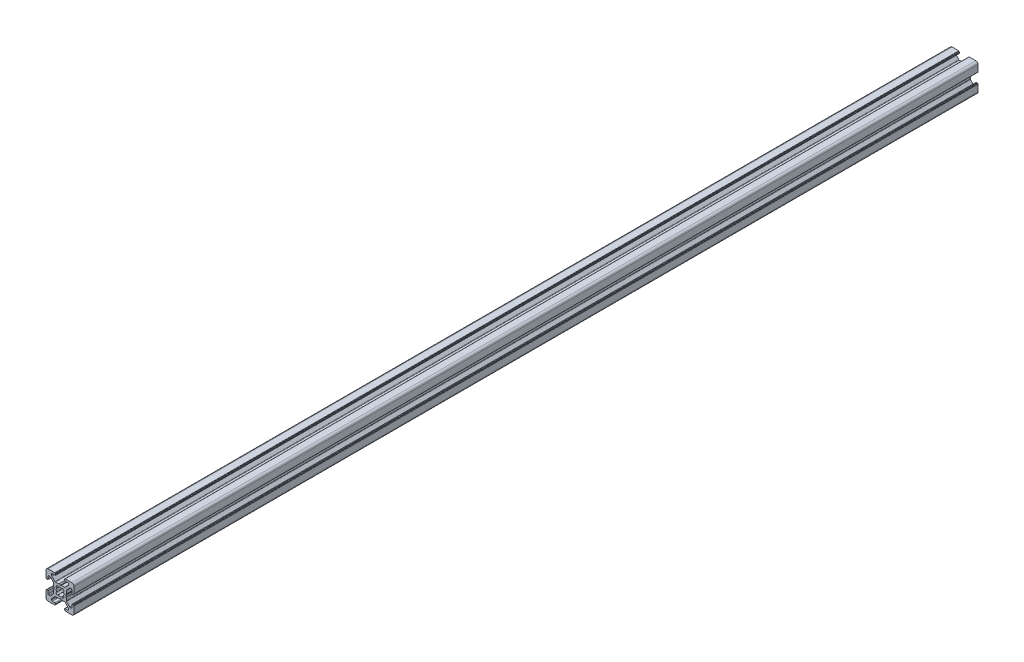
SolidWorks part; units mm, degrees
material "3.1355 (EN-AW 2024)"
ref_plane "Спереди" through (0, 0, 0) normal (0, 0, 1) x (1, 0, 0)
ref_plane "Сверху" through (0, 0, 0) normal (0, 1, 0) x (1, 0, 0)
ref_plane "Справа" through (0, 0, 0) normal (1, 0, 0) x (0, 0, -1)
sketch "Model" plane through (0, 0, 0) normal (0, 0, 1) x (1, 0, 0)
  line L0 (-1.9139, 2.9896) -> (-1.2582, 2.4453)
  line L1 (1.2582, 2.4453) -> (1.9139, 2.9896)
  line L2 (2.9922, 1.9099) -> (2.4453, 1.2582)
  line L3 (2.4453, -1.2582) -> (2.9922, -1.9099)
  line L4 (1.9139, -2.9896) -> (1.2582, -2.4453)
  line L5 (-1.2582, -2.4453) -> (-1.9139, -2.9896)
  line L6 (-2.9922, -1.9099) -> (-2.4453, -1.2582)
  line L7 (-2.4453, 1.2582) -> (-2.9922, 1.9099)
  line L8 (5.6579, 4.5972) -> (5.7096, 4.7904)
  line L9 (5.7096, 4.7904) -> (5.9028, 4.8421)
  line L10 (5.9028, 4.8421) -> (6.9142, 5.8536)
  line L11 (7.2678, 6) -> (8, 6)
  line L12 (8.5, 5.5) -> (8.5, 3.6)
  line L13 (9, 3.1) -> (9.3, 3.1)
  line L14 (9.5, 3.3) -> (9.5, 3.35)
  line L15 (9.7, 3.55) -> (9.8, 3.55)
  line L16 (10, 3.75) -> (10, 8.5)
  line L17 (8.5, 10) -> (3.75, 10)
  line L18 (3.55, 9.8) -> (3.55, 9.7)
  line L19 (3.35, 9.5) -> (3.3, 9.5)
  line L20 (3.1, 9.3) -> (3.1, 9)
  line L21 (3.6, 8.5) -> (5.5, 8.5)
  line L22 (6, 8) -> (6, 7.2678)
  line L23 (5.8536, 6.9142) -> (3.5858, 4.6464)
  line L24 (3.2322, 4.5) -> (0.9536, 4.5)
  line L25 (0.8536, 4.4732) -> (0.1, 4.0381)
  line L26 (-0.1, 4.0381) -> (-0.8536, 4.4732)
  line L27 (-0.9536, 4.5) -> (-3.2322, 4.5)
  line L28 (-3.5858, 4.6464) -> (-5.8536, 6.9142)
  line L29 (-6, 7.2678) -> (-6, 8)
  line L30 (-5.5, 8.5) -> (-3.6, 8.5)
  line L31 (-3.1, 9) -> (-3.1, 9.3)
  line L32 (-3.3, 9.5) -> (-3.35, 9.5)
  line L33 (-3.55, 9.7) -> (-3.55, 9.8)
  line L34 (-3.75, 10) -> (-8.5, 10)
  line L35 (-10, 8.5) -> (-10, 3.75)
  line L36 (-9.8, 3.55) -> (-9.7, 3.55)
  line L37 (-9.5, 3.35) -> (-9.5, 3.3)
  line L38 (-9.3, 3.1) -> (-9, 3.1)
  line L39 (-8.5, 3.6) -> (-8.5, 5.5)
  line L40 (-8, 6) -> (-7.2678, 6)
  line L41 (-6.9142, 5.8536) -> (-4.6464, 3.5858)
  line L42 (-4.5, 3.2322) -> (-4.5, 0.9536)
  line L43 (-4.4732, 0.8536) -> (-4.0381, 0.1)
  line L44 (-4.0381, -0.1) -> (-4.4732, -0.8536)
  line L45 (-4.5, -0.9536) -> (-4.5, -3.2322)
  line L46 (-4.6464, -3.5858) -> (-6.9142, -5.8536)
  line L47 (-7.2678, -6) -> (-8, -6)
  line L48 (-8.5, -5.5) -> (-8.5, -3.6)
  line L49 (-9, -3.1) -> (-9.3, -3.1)
  line L50 (-9.5, -3.3) -> (-9.5, -3.35)
  line L51 (-9.7, -3.55) -> (-9.8, -3.55)
  line L52 (-10, -3.75) -> (-10, -8.5)
  line L53 (-8.5, -10) -> (-3.75, -10)
  line L54 (-3.55, -9.8) -> (-3.55, -9.7)
  line L55 (-3.35, -9.5) -> (-3.3, -9.5)
  line L56 (-3.1, -9.3) -> (-3.1, -9)
  line L57 (-3.6, -8.5) -> (-5.5, -8.5)
  line L58 (-6, -8) -> (-6, -7.2678)
  line L59 (-5.8536, -6.9142) -> (-3.5858, -4.6464)
  line L60 (-3.2322, -4.5) -> (-0.9536, -4.5)
  line L61 (-0.8536, -4.4732) -> (-0.1, -4.0381)
  line L62 (0.1, -4.0381) -> (0.8536, -4.4732)
  line L63 (0.9536, -4.5) -> (3.2322, -4.5)
  line L64 (3.5858, -4.6464) -> (5.8536, -6.9142)
  line L65 (6, -7.2678) -> (6, -8)
  line L66 (5.5, -8.5) -> (3.6, -8.5)
  line L67 (3.1, -9) -> (3.1, -9.3)
  line L68 (3.3, -9.5) -> (3.35, -9.5)
  line L69 (3.55, -9.7) -> (3.55, -9.8)
  line L70 (3.75, -10) -> (8.5, -10)
  line L71 (10, -8.5) -> (10, -3.75)
  line L72 (9.8, -3.55) -> (9.7, -3.55)
  line L73 (9.5, -3.35) -> (9.5, -3.3)
  line L74 (9.3, -3.1) -> (9, -3.1)
  line L75 (8.5, -3.6) -> (8.5, -5.5)
  line L76 (8, -6) -> (7.2678, -6)
  line L77 (6.9142, -5.8536) -> (4.6464, -3.5858)
  line L78 (4.5, -3.2322) -> (4.5, -0.9536)
  line L79 (4.4732, -0.8536) -> (4.0381, -0.1)
  line L80 (4.0381, 0.1) -> (4.4732, 0.8536)
  line L81 (4.5, 0.9536) -> (4.5, 3.2322)
  line L82 (4.6464, 3.5858) -> (5.6579, 4.5972)
  arc A0 (-1.9139, 2.9896) -> (-2.9922, 1.9099) centre (0, 0) ccw
  arc A1 (1.2582, 2.4453) -> (-1.2582, 2.4453) centre (0, 0) ccw
  arc A2 (2.9922, 1.9099) -> (1.9139, 2.9896) centre (0, 0) ccw
  arc A3 (2.4453, -1.2582) -> (2.4453, 1.2582) centre (0, 0) ccw
  arc A4 (1.9139, -2.9896) -> (2.9922, -1.9099) centre (0, 0) ccw
  arc A5 (-1.2582, -2.4453) -> (1.2582, -2.4453) centre (0, 0) ccw
  arc A6 (-2.9922, -1.9099) -> (-1.9139, -2.9896) centre (0, 0) ccw
  arc A7 (-2.4453, 1.2582) -> (-2.4453, -1.2582) centre (0, 0) ccw
  arc A8 (7.2678, 6) -> (6.9142, 5.8536) centre (7.2678, 5.5) ccw
  arc A9 (8.5, 5.5) -> (8, 6) centre (8, 5.5) ccw
  arc A10 (8.5, 3.6) -> (9, 3.1) centre (9, 3.6) ccw
  arc A11 (9.3, 3.1) -> (9.5, 3.3) centre (9.3, 3.3) ccw
  arc A12 (9.7, 3.55) -> (9.5, 3.35) centre (9.7, 3.35) ccw
  arc A13 (9.8, 3.55) -> (10, 3.75) centre (9.8, 3.75) ccw
  arc A14 (10, 8.5) -> (8.5, 10) centre (8.5, 8.5) ccw
  arc A15 (3.75, 10) -> (3.55, 9.8) centre (3.75, 9.8) ccw
  arc A16 (3.35, 9.5) -> (3.55, 9.7) centre (3.35, 9.7) ccw
  arc A17 (3.3, 9.5) -> (3.1, 9.3) centre (3.3, 9.3) ccw
  arc A18 (3.1, 9) -> (3.6, 8.5) centre (3.6, 9) ccw
  arc A19 (6, 8) -> (5.5, 8.5) centre (5.5, 8) ccw
  arc A20 (5.8536, 6.9142) -> (6, 7.2678) centre (5.5, 7.2678) ccw
  arc A21 (3.2322, 4.5) -> (3.5858, 4.6464) centre (3.2322, 5) ccw
  arc A22 (0.9536, 4.5) -> (0.8536, 4.4732) centre (0.9536, 4.3) ccw
  arc A23 (-0.1, 4.0381) -> (0.1, 4.0381) centre (0, 4.2113) ccw
  arc A24 (-0.8536, 4.4732) -> (-0.9536, 4.5) centre (-0.9536, 4.3) ccw
  arc A25 (-3.5858, 4.6464) -> (-3.2322, 4.5) centre (-3.2322, 5) ccw
  arc A26 (-6, 7.2678) -> (-5.8536, 6.9142) centre (-5.5, 7.2678) ccw
  arc A27 (-5.5, 8.5) -> (-6, 8) centre (-5.5, 8) ccw
  arc A28 (-3.6, 8.5) -> (-3.1, 9) centre (-3.6, 9) ccw
  arc A29 (-3.1, 9.3) -> (-3.3, 9.5) centre (-3.3, 9.3) ccw
  arc A30 (-3.55, 9.7) -> (-3.35, 9.5) centre (-3.35, 9.7) ccw
  arc A31 (-3.55, 9.8) -> (-3.75, 10) centre (-3.75, 9.8) ccw
  arc A32 (-8.5, 10) -> (-10, 8.5) centre (-8.5, 8.5) ccw
  arc A33 (-10, 3.75) -> (-9.8, 3.55) centre (-9.8, 3.75) ccw
  arc A34 (-9.5, 3.35) -> (-9.7, 3.55) centre (-9.7, 3.35) ccw
  arc A35 (-9.5, 3.3) -> (-9.3, 3.1) centre (-9.3, 3.3) ccw
  arc A36 (-9, 3.1) -> (-8.5, 3.6) centre (-9, 3.6) ccw
  arc A37 (-8, 6) -> (-8.5, 5.5) centre (-8, 5.5) ccw
  arc A38 (-6.9142, 5.8536) -> (-7.2678, 6) centre (-7.2678, 5.5) ccw
  arc A39 (-4.5, 3.2322) -> (-4.6464, 3.5858) centre (-5, 3.2322) ccw
  arc A40 (-4.5, 0.9536) -> (-4.4732, 0.8536) centre (-4.3, 0.9536) ccw
  arc A41 (-4.0381, -0.1) -> (-4.0381, 0.1) centre (-4.2113, 0) ccw
  arc A42 (-4.4732, -0.8536) -> (-4.5, -0.9536) centre (-4.3, -0.9536) ccw
  arc A43 (-4.6464, -3.5858) -> (-4.5, -3.2322) centre (-5, -3.2322) ccw
  arc A44 (-7.2678, -6) -> (-6.9142, -5.8536) centre (-7.2678, -5.5) ccw
  arc A45 (-8.5, -5.5) -> (-8, -6) centre (-8, -5.5) ccw
  arc A46 (-8.5, -3.6) -> (-9, -3.1) centre (-9, -3.6) ccw
  arc A47 (-9.3, -3.1) -> (-9.5, -3.3) centre (-9.3, -3.3) ccw
  arc A48 (-9.7, -3.55) -> (-9.5, -3.35) centre (-9.7, -3.35) ccw
  arc A49 (-9.8, -3.55) -> (-10, -3.75) centre (-9.8, -3.75) ccw
  arc A50 (-10, -8.5) -> (-8.5, -10) centre (-8.5, -8.5) ccw
  arc A51 (-3.75, -10) -> (-3.55, -9.8) centre (-3.75, -9.8) ccw
  arc A52 (-3.35, -9.5) -> (-3.55, -9.7) centre (-3.35, -9.7) ccw
  arc A53 (-3.3, -9.5) -> (-3.1, -9.3) centre (-3.3, -9.3) ccw
  arc A54 (-3.1, -9) -> (-3.6, -8.5) centre (-3.6, -9) ccw
  arc A55 (-6, -8) -> (-5.5, -8.5) centre (-5.5, -8) ccw
  arc A56 (-5.8536, -6.9142) -> (-6, -7.2678) centre (-5.5, -7.2678) ccw
  arc A57 (-3.2322, -4.5) -> (-3.5858, -4.6464) centre (-3.2322, -5) ccw
  arc A58 (-0.9536, -4.5) -> (-0.8536, -4.4732) centre (-0.9536, -4.3) ccw
  arc A59 (0.1, -4.0381) -> (-0.1, -4.0381) centre (0, -4.2113) ccw
  arc A60 (0.8536, -4.4732) -> (0.9536, -4.5) centre (0.9536, -4.3) ccw
  arc A61 (3.5858, -4.6464) -> (3.2322, -4.5) centre (3.2322, -5) ccw
  arc A62 (6, -7.2678) -> (5.8536, -6.9142) centre (5.5, -7.2678) ccw
  arc A63 (5.5, -8.5) -> (6, -8) centre (5.5, -8) ccw
  arc A64 (3.6, -8.5) -> (3.1, -9) centre (3.6, -9) ccw
  arc A65 (3.1, -9.3) -> (3.3, -9.5) centre (3.3, -9.3) ccw
  arc A66 (3.55, -9.7) -> (3.35, -9.5) centre (3.35, -9.7) ccw
  arc A67 (3.55, -9.8) -> (3.75, -10) centre (3.75, -9.8) ccw
  arc A68 (8.5, -10) -> (10, -8.5) centre (8.5, -8.5) ccw
  arc A69 (10, -3.75) -> (9.8, -3.55) centre (9.8, -3.75) ccw
  arc A70 (9.5, -3.35) -> (9.7, -3.55) centre (9.7, -3.35) ccw
  arc A71 (9.5, -3.3) -> (9.3, -3.1) centre (9.3, -3.3) ccw
  arc A72 (9, -3.1) -> (8.5, -3.6) centre (9, -3.6) ccw
  arc A73 (8, -6) -> (8.5, -5.5) centre (8, -5.5) ccw
  arc A74 (6.9142, -5.8536) -> (7.2678, -6) centre (7.2678, -5.5) ccw
  arc A75 (4.5, -3.2322) -> (4.6464, -3.5858) centre (5, -3.2322) ccw
  arc A76 (4.5, -0.9536) -> (4.4732, -0.8536) centre (4.3, -0.9536) ccw
  arc A77 (4.0381, 0.1) -> (4.0381, -0.1) centre (4.2113, 0) ccw
  arc A78 (4.4732, 0.8536) -> (4.5, 0.9536) centre (4.3, 0.9536) ccw
  arc A79 (4.6464, 3.5858) -> (4.5, 3.2322) centre (5, 3.2322) ccw
  dimension "D1" = 20
extrude "База" add sketch "Model" against normal mid plane 645
